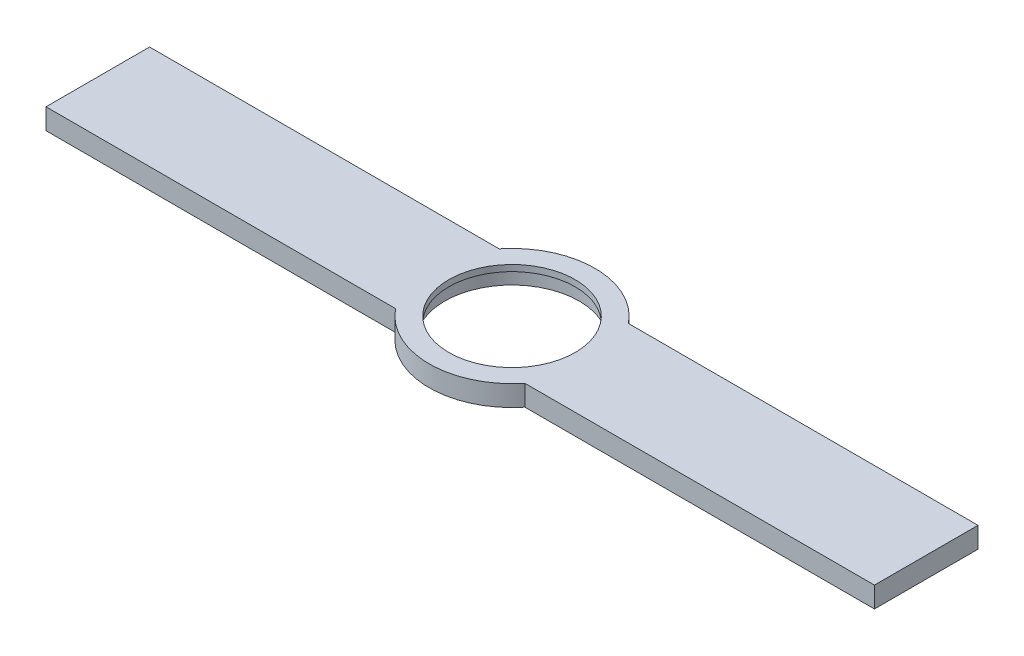
SolidWorks part; units mm, degrees
ref_plane "Front Plane" through (0, 0, 0) normal (0, 0, 1) x (1, 0, 0)
ref_plane "Top Plane" through (0, 0, 0) normal (0, 1, 0) x (1, 0, 0)
ref_plane "Right Plane" through (0, 0, 0) normal (1, 0, 0) x (0, 0, -1)
sketch "Sketch1" plane through (0, 0, 0) normal (0, 1, 0) x (1, 0, 0)
  line L1 (-200, 25) -> (200, 25)
  line L2 (-200, 25) -> (-200, -25)
  line L3 (-200, -25) -> (200, -25)
  line L4 (200, 25) -> (200, -25)
  line L5 (-200, 25) -> (200, -25) construction
  line L6 (-200, -25) -> (200, 25) construction
  circle A0 centre (0, 0) radius 40
  point P0 (0, 0)
  dimension "D3" = 80
  dimension "D1" = 400
  dimension "D2" = 50
extrude "Boss-Extrude1" add sketch "Sketch1" along normal blind 10 contours L1 A0 | L3 A0 L1 | A0 L1 L2 L3 | A0 L3 L4 L1 | L3 A0
sketch "Sketch4" plane through (0, 10, 0) normal (0, 1, 0) x (1, 0, 0)
  circle A0 centre (0, 0) radius 30.5
  dimension "D1" = 61
sketch "Sketch3" plane through (0, 0, 0) normal (0, -1, 0) x (1, 0, 0)
  circle A0 centre (0, 0) radius 32.5
  dimension "D1" = 65
extrude "Cut-Extrude3" cut sketch "Sketch4" against normal up to next
extrude "Cut-Extrude4" cut sketch "Sketch3" against normal blind 7 contours A0
